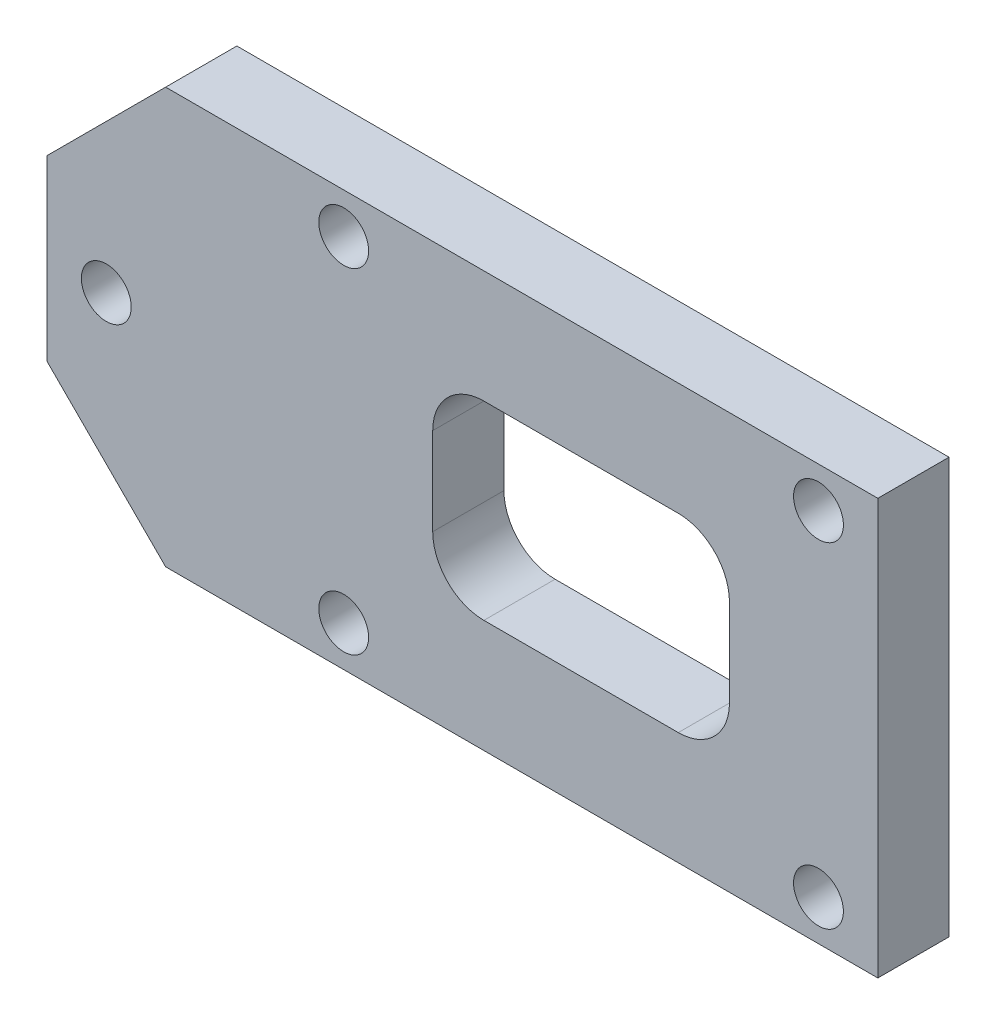
SolidWorks part; units mm, degrees
material "ABS"
ref_plane "Płaszczyzna przednia" through (0, 0, 0) normal (0, 0, 1) x (1, 0, 0)
ref_plane "Płaszczyzna górna" through (0, 0, 0) normal (0, 1, 0) x (1, 0, 0)
ref_plane "Płaszczyzna prawa" through (0, 0, 0) normal (1, 0, 0) x (0, 0, -1)
sketch "Szkic1" plane through (0, 0, 0) normal (0, 0, 1) x (1, 0, 0)
  line L0 (0.0446, 17.5) -> (74.7906, 17.5) construction
  line L1 (10, 0) -> (70, 0)
  line L2 (0, 10) -> (0, 25)
  line L3 (10, 35) -> (70, 35)
  line L4 (70, 0) -> (70, 35)
  line L5 (0, 25) -> (10, 35)
  line L6 (10, 0) -> (0, 10)
  line L8 (53.1889, 9.5) -> (36.8111, 9.5)
  line L9 (57.5, 13.8111) -> (57.5, 21.1889)
  line L10 (53.1889, 25.5) -> (36.8111, 25.5)
  line L11 (32.5, 13.8111) -> (32.5, 21.1889)
  line L12 (57.5, 9.5) -> (32.5, 25.5) construction
  line L13 (57.5, 25.5) -> (32.5, 9.5) construction
  circle A0 centre (65, 31.6) radius 2.1
  circle A1 centre (25, 31.6) radius 2.1
  circle A2 centre (65, 3.4) radius 2.1
  circle A3 centre (25, 3.4) radius 2.1
  circle A4 centre (5, 17.5) radius 2.1
  arc A5 (32.5, 13.8111) -> (36.8111, 9.5) centre (36.8111, 13.8111) ccw
  arc A6 (53.1889, 9.5) -> (57.5, 13.8111) centre (53.1889, 13.8111) ccw
  arc A7 (57.5, 21.1889) -> (53.1889, 25.5) centre (53.1889, 21.1889) ccw
  arc A8 (36.8111, 25.5) -> (32.5, 21.1889) centre (36.8111, 21.1889) ccw
  point P0 (0, 0)
  point P2 (0, 35)
  point P21 (45, 17.5)
  dimension "D3" = 4.2
  dimension "D4" = 14.1
  dimension "D8" = 4.2
  dimension "D9" = 5
  dimension "D15" = 4.3111
  dimension "D1" = 70
  dimension "D2" = 35
  dimension "D5" = 40
  dimension "D6" = 5
  dimension "D7" = 17.5
  dimension "D10" = 25
  dimension "D11" = 25
  dimension "D14" = 16
extrude "Dodanie-wyciągnięcie1" add sketch "Szkic1" along normal blind 6
